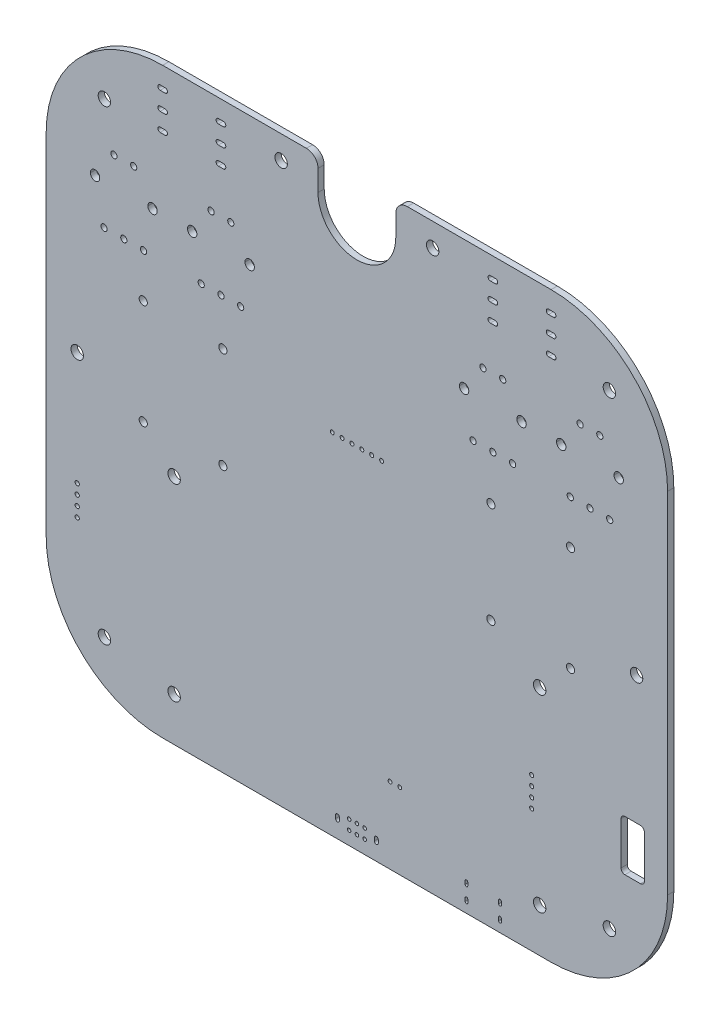
SolidWorks part; units mm, degrees
ref_plane "前视基准面" through (0, 0, 0) normal (0, 0, 1) x (1, 0, 0)
ref_plane "上视基准面" through (0, 0, 0) normal (0, 1, 0) x (1, 0, 0)
ref_plane "右视基准面" through (0, 0, 0) normal (1, 0, 0) x (0, 0, -1)
other "Configuration Table"
ref_plane "基准面1" through (0, 0, 1.6001) normal (0, 0, 1) x (1, 0, 0)
sketch "草图1" plane through (0, 0, 1.6001) normal (0, 0, 1) x (1, 0, 0)
  line L0 (148.0003, 30.0301) -> (148.0003, 41.0301)
  line L1 (149.0003, 42.0301) -> (153.0003, 42.0301)
  line L2 (154.0003, 41.0301) -> (154.0003, 30.0301)
  line L3 (153.0003, 29.0301) -> (149.0003, 29.0301)
  line L4 (148.6003, 116.8003) -> (148.6003, 116.7003)
  line L5 (146.2003, 116.7003) -> (146.2003, 116.8003)
  line L6 (133.8003, 116.8003) -> (133.8003, 116.7003)
  line L7 (131.4003, 116.7003) -> (131.4003, 116.8003)
  line L8 (130.6503, 139.4003) -> (129.3503, 139.4003)
  line L9 (129.3503, 140.6003) -> (130.6503, 140.6003)
  line L10 (130.6503, 134.7003) -> (129.3503, 134.7003)
  line L11 (129.3503, 135.9003) -> (130.6503, 135.9003)
  line L12 (130.6503, 144.1003) -> (129.3503, 144.1003)
  line L13 (129.3503, 145.3003) -> (130.6503, 145.3003)
  line L14 (123.6002, 116.8003) -> (123.6002, 116.7003)
  line L15 (121.2002, 116.7003) -> (121.2002, 116.8003)
  line L16 (117.1933, 7.126) -> (117.1933, 6.3259)
  line L17 (116.4923, 6.3259) -> (116.4923, 7.126)
  line L18 (117.1933, 3.3261) -> (117.1933, 2.526)
  line L19 (116.4923, 2.526) -> (116.4923, 3.3261)
  line L20 (115.6502, 139.4003) -> (114.3502, 139.4003)
  line L21 (114.3502, 140.6003) -> (115.6502, 140.6003)
  line L22 (115.6502, 134.7003) -> (114.3502, 134.7003)
  line L23 (114.3502, 135.9003) -> (115.6502, 135.9003)
  line L24 (115.6502, 144.1003) -> (114.3502, 144.1003)
  line L25 (114.3502, 145.3003) -> (115.6502, 145.3003)
  line L26 (108.5522, 7.126) -> (108.5522, 6.3259)
  line L27 (107.8512, 6.3259) -> (107.8512, 7.126)
  line L28 (108.5522, 3.3261) -> (108.5522, 2.526)
  line L29 (107.8512, 2.526) -> (107.8512, 3.3261)
  line L30 (108.8002, 116.8003) -> (108.8002, 116.7003)
  line L31 (106.4002, 116.7003) -> (106.4002, 116.8003)
  line L32 (85.5002, 5.099) -> (85.5002, 4.299)
  line L33 (84.5002, 4.299) -> (84.5002, 5.099)
  line L34 (75.5001, 5.099) -> (75.5001, 4.299)
  line L35 (74.5001, 4.299) -> (74.5001, 5.099)
  line L36 (53.6001, 116.8003) -> (53.6001, 116.7003)
  line L37 (51.2001, 116.7003) -> (51.2001, 116.8003)
  line L38 (45.6501, 144.1003) -> (44.3501, 144.1003)
  line L39 (44.3501, 145.3003) -> (45.6501, 145.3003)
  line L40 (45.6501, 139.4003) -> (44.3501, 139.4003)
  line L41 (44.3501, 140.6003) -> (45.6501, 140.6003)
  line L42 (45.6501, 134.7003) -> (44.3501, 134.7003)
  line L43 (44.3501, 135.9003) -> (45.6501, 135.9003)
  line L44 (38.8001, 116.8003) -> (38.8001, 116.7003)
  line L45 (36.4001, 116.7003) -> (36.4001, 116.8003)
  line L46 (30.6501, 139.4003) -> (29.3501, 139.4003)
  line L47 (29.3501, 140.6003) -> (30.6501, 140.6003)
  line L48 (30.6501, 134.7003) -> (29.3501, 134.7003)
  line L49 (29.3501, 135.9003) -> (30.6501, 135.9003)
  line L50 (30.6501, 144.1003) -> (29.3501, 144.1003)
  line L51 (29.3501, 145.3003) -> (30.6501, 145.3003)
  line L52 (28.6, 116.8003) -> (28.6, 116.7003)
  line L53 (26.2, 116.7003) -> (26.2, 116.8003)
  line L54 (13.8, 116.8003) -> (13.8, 116.7003)
  line L55 (11.4, 116.7003) -> (11.4, 116.8003)
  line L56 (0.0127, 120.0002) -> (0.0127, 30.0001)
  line L57 (30.0001, 0.0127) -> (130.0003, 0.0127)
  line L58 (159.9876, 30.0001) -> (159.9876, 120.0002)
  line L59 (130.0003, 149.9876) -> (93.0002, 149.9876)
  line L60 (90.0129, 147.0003) -> (90.0129, 141.6253)
  line L61 (69.9874, 141.6253) -> (69.9874, 147.0003)
  line L62 (67.0001, 149.9876) -> (30.0001, 149.9876)
  circle A0 centre (152.0003, 75.0001) radius 1.6002
  arc A1 (149.0003, 29.0301) -> (148.0003, 30.0301) centre (149.0003, 30.0301) cw
  arc A2 (148.0003, 41.0301) -> (149.0003, 42.0301) centre (149.0003, 41.0301) cw
  arc A3 (153.0003, 42.0301) -> (154.0003, 41.0301) centre (153.0003, 41.0301) cw
  arc A4 (154.0003, 30.0301) -> (153.0003, 29.0301) centre (153.0003, 30.0301) cw
  arc A5 (148.6003, 116.7003) -> (146.2003, 116.7003) centre (147.4003, 116.7003) cw
  arc A6 (146.2003, 116.8003) -> (148.6003, 116.8003) centre (147.4003, 116.8003) cw
  circle A7 centre (145.0803, 106.2504) radius 0.8
  circle A8 centre (145.0003, 15) radius 1.6002
  circle A9 centre (145.0003, 135.0003) radius 1.6002
  circle A10 centre (142.5403, 123.7503) radius 0.8
  circle A11 centre (140.0003, 106.2502) radius 0.8
  circle A12 centre (137.4603, 123.7503) radius 0.8
  circle A13 centre (134.9203, 106.2504) radius 0.8
  circle A14 centre (135.0003, 95.0002) radius 1.05
  circle A15 centre (135.0003, 68.0141) radius 1.05
  arc A16 (133.8003, 116.7003) -> (131.4003, 116.7003) centre (132.6003, 116.7003) cw
  arc A17 (131.4003, 116.8003) -> (133.8003, 116.8003) centre (132.6003, 116.8003) cw
  arc A18 (129.3503, 139.4003) -> (129.3503, 140.6003) centre (129.3503, 140.0003) cw
  arc A19 (130.6503, 140.6003) -> (130.6503, 139.4003) centre (130.6503, 140.0003) cw
  arc A20 (129.3503, 134.7003) -> (129.3503, 135.9003) centre (129.3503, 135.3003) cw
  arc A21 (130.6503, 135.9003) -> (130.6503, 134.7003) centre (130.6503, 135.3003) cw
  arc A22 (129.3503, 144.1003) -> (129.3503, 145.3003) centre (129.3503, 144.7003) cw
  arc A23 (130.6503, 145.3003) -> (130.6503, 144.1003) centre (130.6503, 144.7003) cw
  circle A24 centre (127.0503, 11.26) radius 1.6
  circle A25 centre (127.0503, 59.8001) radius 1.6
  circle A26 centre (125, 36.7801) radius 0.525
  circle A27 centre (125, 34.2801) radius 0.525
  circle A28 centre (125, 31.7801) radius 0.525
  circle A29 centre (125, 39.2801) radius 0.525
  arc A30 (123.6002, 116.7003) -> (121.2002, 116.7003) centre (122.4002, 116.7003) cw
  arc A31 (121.2002, 116.8003) -> (123.6002, 116.8003) centre (122.4002, 116.8003) cw
  circle A32 centre (120.0802, 106.2504) radius 0.8
  circle A33 centre (117.5402, 123.7503) radius 0.8
  arc A34 (117.1933, 6.3259) -> (116.4923, 6.3259) centre (116.8428, 6.3259) cw
  arc A35 (116.4923, 7.126) -> (117.1933, 7.126) centre (116.8428, 7.126) cw
  arc A36 (117.1933, 2.526) -> (116.4923, 2.526) centre (116.8428, 2.526) cw
  arc A37 (116.4923, 3.3261) -> (117.1933, 3.3261) centre (116.8428, 3.3261) cw
  circle A38 centre (115.0002, 106.2502) radius 0.8
  arc A39 (114.3502, 139.4003) -> (114.3502, 140.6003) centre (114.3502, 140.0003) cw
  arc A40 (115.6502, 140.6003) -> (115.6502, 139.4003) centre (115.6502, 140.0003) cw
  arc A41 (114.3502, 134.7003) -> (114.3502, 135.9003) centre (114.3502, 135.3003) cw
  arc A42 (115.6502, 135.9003) -> (115.6502, 134.7003) centre (115.6502, 135.3003) cw
  arc A43 (114.3502, 144.1003) -> (114.3502, 145.3003) centre (114.3502, 144.7003) cw
  arc A44 (115.6502, 145.3003) -> (115.6502, 144.1003) centre (115.6502, 144.7003) cw
  circle A45 centre (114.5002, 94.5002) radius 1.05
  circle A46 centre (114.5002, 68.5001) radius 1.05
  circle A47 centre (112.4602, 123.7503) radius 0.8
  circle A48 centre (109.9202, 106.2504) radius 0.8
  arc A49 (108.5522, 6.3259) -> (107.8512, 6.3259) centre (108.2017, 6.3259) cw
  arc A50 (107.8512, 7.126) -> (108.5522, 7.126) centre (108.2017, 7.126) cw
  arc A51 (108.5522, 2.526) -> (107.8512, 2.526) centre (108.2017, 2.526) cw
  arc A52 (107.8512, 3.3261) -> (108.5522, 3.3261) centre (108.2017, 3.3261) cw
  arc A53 (108.8002, 116.7003) -> (106.4002, 116.7003) centre (107.6002, 116.7003) cw
  arc A54 (106.4002, 116.8003) -> (108.8002, 116.8003) centre (107.6002, 116.8003) cw
  circle A55 centre (99.5002, 144.0003) radius 1.6
  circle A56 centre (91.0392, 19.558) radius 0.5
  circle A57 centre (88.5392, 19.558) radius 0.5
  circle A58 centre (86.3502, 90.0002) radius 0.51
  arc A59 (85.5002, 4.299) -> (84.5002, 4.299) centre (85.0002, 4.299) cw
  arc A60 (84.5002, 5.099) -> (85.5002, 5.099) centre (85.0002, 5.099) cw
  circle A61 centre (83.8102, 90.0002) radius 0.51
  circle A62 centre (82.0002, 3.449) radius 0.4572
  circle A63 centre (82.0002, 5.949) radius 0.4572
  circle A64 centre (81.2702, 90.0002) radius 0.51
  circle A65 centre (80.0002, 3.449) radius 0.4572
  circle A66 centre (80.0002, 5.949) radius 0.4572
  circle A67 centre (78.7302, 90.0002) radius 0.51
  circle A68 centre (78.0002, 5.949) radius 0.4572
  circle A69 centre (78.0002, 3.449) radius 0.4572
  circle A70 centre (76.1902, 90.0002) radius 0.51
  arc A71 (75.5001, 4.299) -> (74.5001, 4.299) centre (75.0001, 4.299) cw
  arc A72 (74.5001, 5.099) -> (75.5001, 5.099) centre (75.0001, 5.099) cw
  circle A73 centre (73.6501, 90.0002) radius 0.51
  circle A74 centre (60.5001, 144.0003) radius 1.6
  arc A75 (53.6001, 116.7003) -> (51.2001, 116.7003) centre (52.4001, 116.7003) cw
  arc A76 (51.2001, 116.8003) -> (53.6001, 116.8003) centre (52.4001, 116.8003) cw
  circle A77 centre (50.0801, 106.2504) radius 0.8
  circle A78 centre (47.5401, 123.7503) radius 0.8
  circle A79 centre (45.5001, 94.5142) radius 1.05
  circle A80 centre (45.5001, 68.5141) radius 1.05
  circle A81 centre (45.0001, 106.2502) radius 0.8
  arc A82 (44.3501, 144.1003) -> (44.3501, 145.3003) centre (44.3501, 144.7003) cw
  arc A83 (45.6501, 145.3003) -> (45.6501, 144.1003) centre (45.6501, 144.7003) cw
  arc A84 (44.3501, 139.4003) -> (44.3501, 140.6003) centre (44.3501, 140.0003) cw
  arc A85 (45.6501, 140.6003) -> (45.6501, 139.4003) centre (45.6501, 140.0003) cw
  arc A86 (44.3501, 134.7003) -> (44.3501, 135.9003) centre (44.3501, 135.3003) cw
  arc A87 (45.6501, 135.9003) -> (45.6501, 134.7003) centre (45.6501, 135.3003) cw
  circle A88 centre (42.4601, 123.7503) radius 0.8
  circle A89 centre (39.9201, 106.2504) radius 0.8
  arc A90 (38.8001, 116.7003) -> (36.4001, 116.7003) centre (37.6001, 116.7003) cw
  arc A91 (36.4001, 116.8003) -> (38.8001, 116.8003) centre (37.6001, 116.8003) cw
  circle A92 centre (32.9501, 11.26) radius 1.6
  circle A93 centre (32.9501, 59.8001) radius 1.6
  arc A94 (29.3501, 139.4003) -> (29.3501, 140.6003) centre (29.3501, 140.0003) cw
  arc A95 (30.6501, 140.6003) -> (30.6501, 139.4003) centre (30.6501, 140.0003) cw
  arc A96 (29.3501, 134.7003) -> (29.3501, 135.9003) centre (29.3501, 135.3003) cw
  arc A97 (30.6501, 135.9003) -> (30.6501, 134.7003) centre (30.6501, 135.3003) cw
  arc A98 (29.3501, 144.1003) -> (29.3501, 145.3003) centre (29.3501, 144.7003) cw
  arc A99 (30.6501, 145.3003) -> (30.6501, 144.1003) centre (30.6501, 144.7003) cw
  arc A100 (28.6, 116.7003) -> (26.2, 116.7003) centre (27.4, 116.7003) cw
  arc A101 (26.2, 116.8003) -> (28.6, 116.8003) centre (27.4, 116.8003) cw
  circle A102 centre (25.0801, 106.2504) radius 0.8
  circle A103 centre (25.0001, 95.0002) radius 1.05
  circle A104 centre (25.0001, 68.0141) radius 1.05
  circle A105 centre (22.54, 123.7503) radius 0.8
  circle A106 centre (20, 106.2502) radius 0.8
  circle A107 centre (17.46, 123.7503) radius 0.8
  circle A108 centre (14.92, 106.2504) radius 0.8
  circle A109 centre (15, 15) radius 1.6002
  circle A110 centre (15, 135.0003) radius 1.6002
  arc A111 (13.8, 116.7003) -> (11.4, 116.7003) centre (12.6, 116.7003) cw
  arc A112 (11.4, 116.8003) -> (13.8, 116.8003) centre (12.6, 116.8003) cw
  circle A113 centre (8, 38.1901) radius 0.55
  circle A114 centre (8, 40.7301) radius 0.55
  circle A115 centre (8, 43.2701) radius 0.55
  circle A116 centre (8, 45.8101) radius 0.55
  circle A117 centre (8, 75.0001) radius 1.6002
  arc A118 (0.0127, 30.0001) -> (30.0001, 0.0127) centre (30.0001, 30.0001) ccw
  arc A119 (130.0003, 0.0127) -> (159.9876, 30.0001) centre (130.0003, 30.0001) ccw
  arc A120 (159.9876, 120.0002) -> (130.0003, 149.9876) centre (130.0003, 120.0002) ccw
  arc A121 (93.0002, 149.9876) -> (90.0129, 147.0003) centre (93.0002, 147.0003) ccw
  arc A122 (90.0129, 141.6253) -> (69.9874, 141.6253) centre (80.0002, 141.6253) cw
  arc A123 (69.9874, 147.0003) -> (67.0001, 149.9876) centre (67.0001, 147.0003) ccw
  arc A124 (30.0001, 149.9876) -> (0.0127, 120.0002) centre (30.0001, 120.0002) ccw
extrude "凸台-拉伸1" add sketch "草图1" against normal blind 1.6001
